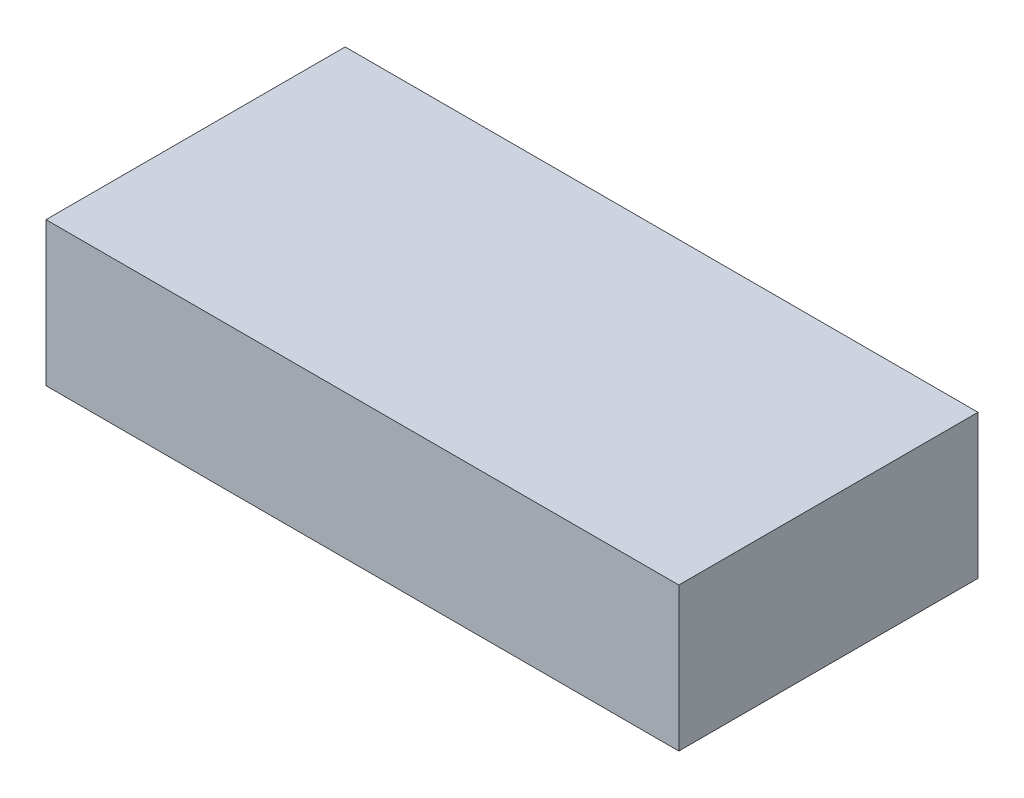
SolidWorks part; units mm, degrees
ref_plane "Front" through (0, 0, 0) normal (0, 0, 1) x (1, 0, 0)
ref_plane "Top" through (0, 0, 0) normal (0, 1, 0) x (1, 0, 0)
ref_plane "Right" through (0, 0, 0) normal (1, 0, 0) x (0, 0, -1)
sketch "Esquisse1" plane through (0, 0, 0) normal (0, 1, 0) x (1, 0, 0)
  line L1 (-55, -26) -> (55, -26)
  line L2 (-55, -26) -> (-55, 26)
  line L3 (-55, 26) -> (55, 26)
  line L4 (55, -26) -> (55, 26)
  line L5 (0, 26) -> (0, -26) construction
  line L6 (-55, 0) -> (55, 0) construction
  point P0 (0, 0)
  dimension "D1" = 52
  dimension "D2" = 110
extrude "Boss.-Extru.1" add sketch "Esquisse1" along normal blind 25
